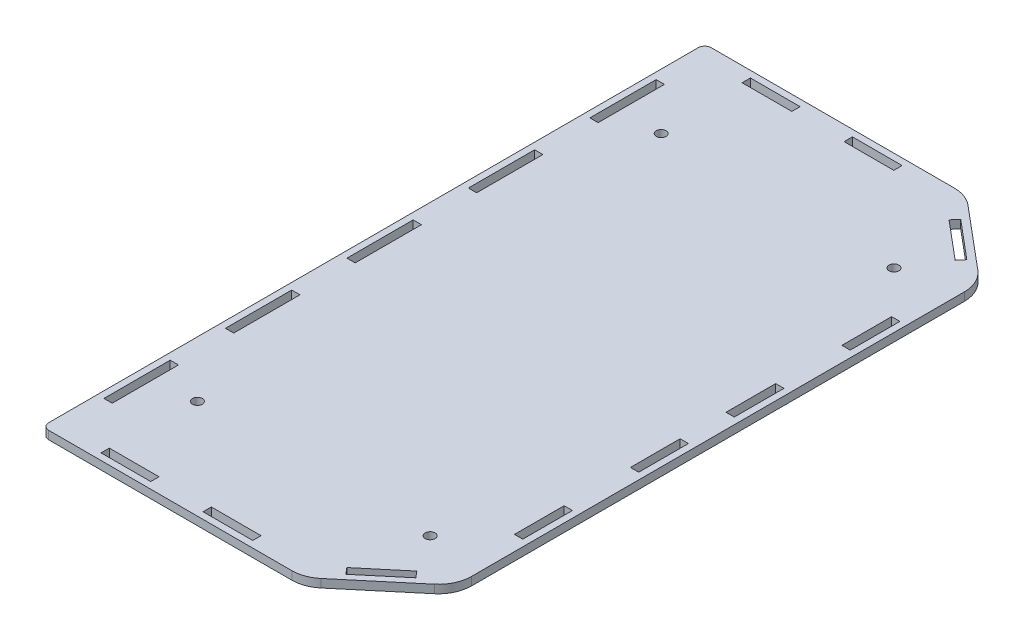
SolidWorks part; units mm, degrees
material "Maple"
ref_plane "Front Plane" through (0, 0, 0) normal (0, 0, 1) x (1, 0, 0)
ref_plane "Top Plane" through (0, 0, 0) normal (0, 1, 0) x (1, 0, 0)
ref_plane "Right Plane" through (0, 0, 0) normal (1, 0, 0) x (0, 0, -1)
sketch "Sketch1" plane through (0, 0, 0) normal (0, 1, 0) x (1, 0, 0)
  line L1 (52, -100) -> (-52, -100) construction
  line L2 (52, -100) -> (52, 100) construction
  line L3 (52, 100) -> (-52, 100) construction
  line L4 (-52, -100) -> (-52, 100) construction
  line L5 (52, -100) -> (-52, 100) construction
  line L6 (52, 100) -> (-52, -100) construction
  line L12 (-36.21, -96.75) -> (-52, -96.75) construction
  line L13 (-36.21, -98) -> (-21.21, -98)
  line L14 (-36.21, -98) -> (-36.21, -95.5)
  line L15 (-36.21, -95.5) -> (-21.21, -95.5)
  line L16 (-21.21, -98) -> (-21.21, -95.5)
  line L17 (-36.21, -98) -> (-21.21, -95.5) construction
  line L18 (-36.21, -95.5) -> (-21.21, -98) construction
  line L19 (-5.42, -98) -> (9.58, -98)
  line L20 (-5.42, -98) -> (-5.42, -95.5)
  line L21 (-5.42, -95.5) -> (9.58, -95.5)
  line L22 (9.58, -98) -> (9.58, -95.5)
  line L23 (-5.42, -98) -> (9.58, -95.5) construction
  line L24 (-5.42, -95.5) -> (9.58, -98) construction
  line L29 (-52, -100) -> (27, -100)
  line L30 (27, -100) -> (52, -79.0225)
  line L31 (-21.21, -96.75) -> (-5.42, -96.75) construction
  line L32 (9.58, -96.75) -> (25.37, -96.75) construction
  line L33 (52, -79.0225) -> (52, 79.0225)
  line L34 (-52, -100) -> (-52, 100)
  line L35 (-28.71, 0) -> (22.6314, 0) construction
  line L36 (-36.21, 98) -> (-36.21, 95.5)
  line L37 (-36.21, 98) -> (-21.21, 98)
  line L38 (-21.21, 98) -> (-21.21, 95.5)
  line L39 (-36.21, 95.5) -> (-21.21, 95.5)
  line L40 (-5.42, 98) -> (-5.42, 95.5)
  line L41 (-5.42, 98) -> (9.58, 98)
  line L42 (9.58, 98) -> (9.58, 95.5)
  line L43 (-5.42, 95.5) -> (9.58, 95.5)
  line L44 (27, 100) -> (52, 79.0225)
  line L45 (-52, 100) -> (27, 100)
  line L46 (30.8621, -90.885) -> (32.4691, -92.8001)
  line L47 (32.4691, -92.8001) -> (43.9598, -83.1583)
  line L48 (43.9598, -83.1583) -> (42.3528, -81.2431)
  line L49 (42.3528, -81.2431) -> (30.8621, -90.885)
  line L50 (38.2144, -87.9792) -> (39.5, -89.5113) construction
  line L52 (30.8621, -90.885) -> (25.37, -95.4934)
  line L53 (25.37, -95.4934) -> (9.58, -95.5)
  line L54 (42.3528, -81.2431) -> (47.5, -76.9241) construction
  line L55 (47.5, -76.9241) -> (47.5, -67.3903) construction
  line L56 (47.5, 21.9241) -> (50, 21.9241)
  line L57 (50, -56.9241) -> (47.5, -56.9241)
  line L58 (50, -56.9241) -> (50, -41.9241)
  line L59 (50, -41.9241) -> (47.5, -41.9241)
  line L60 (47.5, -56.9241) -> (47.5, -41.9241)
  line L61 (50, -56.9241) -> (47.5, -41.9241) construction
  line L62 (50, -41.9241) -> (47.5, -56.9241) construction
  line L63 (47.5, -21.9241) -> (50, -21.9241)
  line L64 (47.5, -21.9241) -> (47.5, -6.9241)
  line L65 (47.5, -6.9241) -> (50, -6.9241)
  line L66 (50, -21.9241) -> (50, -6.9241)
  line L67 (47.5, -21.9241) -> (50, -6.9241) construction
  line L68 (47.5, -6.9241) -> (50, -21.9241) construction
  line L69 (50, 21.9241) -> (50, 6.9241)
  line L70 (47.5, 6.9241) -> (50, 6.9241)
  line L71 (47.5, 21.9241) -> (47.5, 6.9241)
  line L72 (50, 56.9241) -> (47.5, 56.9241)
  line L73 (50, 56.9241) -> (50, 41.9241)
  line L74 (50, 41.9241) -> (47.5, 41.9241)
  line L75 (47.5, 56.9241) -> (47.5, 41.9241)
  line L76 (42.3528, 81.2431) -> (30.8621, 90.885)
  line L77 (43.9598, 83.1583) -> (42.3528, 81.2431)
  line L78 (32.4691, 92.8001) -> (43.9598, 83.1583)
  line L79 (30.8621, 90.885) -> (32.4691, 92.8001)
  line L80 (-50, -46.6667) -> (-50, -26.6667)
  line L81 (-50, -83.3333) -> (-47.5, -83.3333)
  line L82 (-50, -83.3333) -> (-50, -63.3333)
  line L83 (-50, -63.3333) -> (-47.5, -63.3333)
  line L84 (-47.5, -83.3333) -> (-47.5, -63.3333)
  line L85 (-50, -83.3333) -> (-47.5, -63.3333) construction
  line L86 (-50, -63.3333) -> (-47.5, -83.3333) construction
  line L87 (-50, -46.6667) -> (-47.5, -46.6667)
  line L88 (-47.5, -46.6667) -> (-47.5, -26.6667)
  line L89 (-50, -26.6667) -> (-47.5, -26.6667)
  line L90 (-50, -10) -> (-50, 10)
  line L91 (-50, -10) -> (-47.5, -10)
  line L92 (-47.5, -10) -> (-47.5, 10)
  line L93 (-50, 10) -> (-47.5, 10)
  line L94 (-50, 26.6667) -> (-50, 46.6667)
  line L95 (-50, 26.6667) -> (-47.5, 26.6667)
  line L96 (-47.5, 26.6667) -> (-47.5, 46.6667)
  line L97 (-50, 46.6667) -> (-47.5, 46.6667)
  line L98 (-50, 63.3333) -> (-50, 83.3333)
  line L99 (-50, 63.3333) -> (-47.5, 63.3333)
  line L100 (-47.5, 63.3333) -> (-47.5, 83.3333)
  line L101 (-50, 83.3333) -> (-47.5, 83.3333)
  line L102 (-48.75, -83.3333) -> (-48.75, -100) construction
  line L103 (-48.75, -63.3333) -> (-48.75, -46.6667) construction
  line L104 (-48.75, 83.3333) -> (-48.75, 100) construction
  line L105 (0, -26.965) -> (0, 32.9312) construction
  line L106 (-28.6967, -26.965) -> (45.7033, -26.965) construction
  circle A4 centre (35.1272, -70) radius 1.5 construction
  circle A5 centre (35.1272, -70) radius 1.5
  circle A6 centre (35.1272, 70) radius 1.5 construction
  circle A7 centre (35.1272, 70) radius 1.5
  circle A8 centre (-35.1272, 70) radius 1.5
  circle A9 centre (-35.1272, -70) radius 1.5
  point P0 (0, 0)
  point P6 (2.08, -96.75)
  point P12 (-28.71, -96.75)
  point P37 (52, 0)
  point P38 (-52, 0)
  point P40 (39.5, -89.5113)
  point P45 (48.75, -49.4241)
  point P53 (48.75, -14.4241)
  point P70 (-48.75, -73.3333)
  point P101 (0, 0)
  dimension "D1" = 104
  dimension "D2" = 200
  dimension "D3" = 2.5
  dimension "D4" = 2
  dimension "D5" = 15
  dimension "D6" = 15.79
  dimension "D7" = 130
  dimension "D8" = 25
  dimension "D9" = 2
  dimension "D10" = 4.5
  dimension "D11" = 15
  dimension "D12" = 20
  dimension "D13" = 20
  dimension "D14" = 2.5
  dimension "D15" = 2
  dimension "D16" = 20
  dimension "D17" = 2.5
  dimension "D18" = 2
  dimension "D19" = 5
extrude "Boss-Extrude1" add sketch "Sketch1" along normal mid plane 2.5
fillet "Fillet1" radius 10 4 edges at (52, 0, -79.0225) (27, 0, -100) (27, 0, 100) (52, 0, 79.0225)
fillet "Fillet2" radius 2 2 edges at (-52, 0, 100) (-52, 0, -100)
